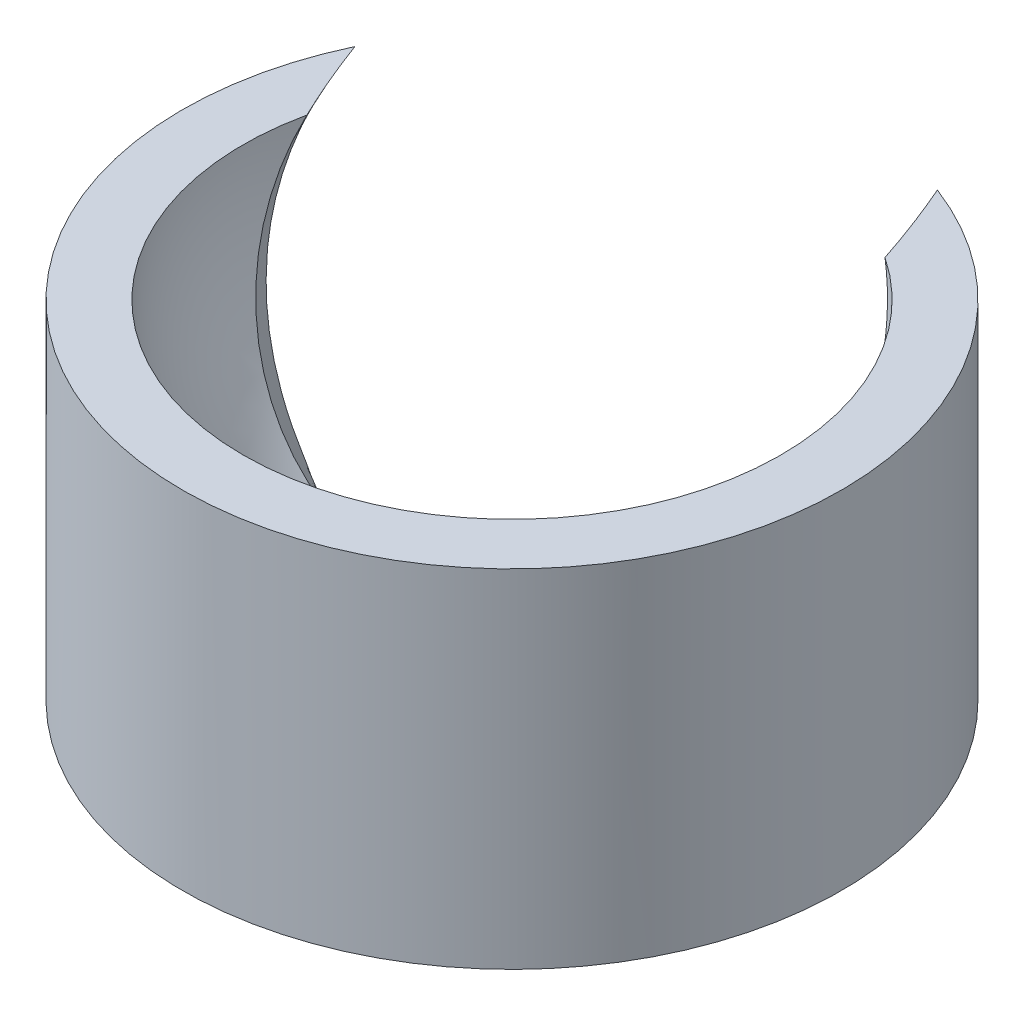
SolidWorks part; units mm, degrees
other "Moving Steel Cup Liner 3"
other "Moving Steel Cup Liner 3 Left"
ref_plane "Front Plane" through (0, 0, 0) normal (0, 0, 1) x (1, 0, 0)
ref_plane "Top Plane" through (0, 0, 0) normal (0, 1, 0) x (1, 0, 0)
ref_plane "Right Plane" through (0, 0, 0) normal (1, 0, 0) x (0, 0, -1)
sketch3d "Keyed Back Sketch datum points"
  point P0 (-56.2917, -97, 0)
  point P1 (-46.2917, -97, 0)
  point P2 (-56.2917, -97, 10)
ref_plane "Keyed Back Sketch plane" through (0, -97, 0) normal (0, -1, 0) x (-1, 0, 0)
sketch "Keyed Back Sketch" plane through (0, -97, 0) normal (0, -1, 0) x (-1, 0, 0)
  line L0 (59.8116, -28.5681) -> (55.7718, -26.2357)
  arc A0 (55.7718, -26.2357) -> (59.8116, -28.5681) centre (56.2917, -30) ccw
extrude "Keyed Back" add sketch "Keyed Back Sketch" along normal blind 0.7 separate body
sketch3d "Cup Blank Sketch datum points"
  point P0 (-56.2917, -97.7, 0)
  point P1 (-46.2917, -97.7, 0)
  point P2 (-56.2917, -97.7, 10)
ref_plane "Cup Blank Sketch plane" through (0, -97.7, 0) normal (0, -1, 0) x (-1, 0, 0)
sketch "Cup Blank Sketch" plane through (0, -97.7, 0) normal (0, -1, 0) x (-1, 0, 0)
  circle A0 centre (56.2917, -30) radius 3.8
extrude "Cup Blank" add sketch "Cup Blank Sketch" along normal blind 3.3
sketch3d "Spherical Bearing Seat axis line"
  line L0 (-56.2917, -101, 20) -> (-56.2917, -101, 40) construction
ref_axis "Spherical Bearing Seat axis" through (-56.2917, -101, 20) along (0, 0, 1)
sketch3d "Spherical Bearing Seat profile datum points"
  point P0 (-56.2917, -101, 30)
  point P1 (-46.2917, -101, 30)
  point P2 (-56.2917, -101, 40)
ref_plane "Spherical Bearing Seat profile plane" through (0, -101, 0) normal (0, -1, 0) x (-1, 0, 0)
sketch "Spherical Bearing Seat profile" plane through (0, -101, 0) normal (0, -1, 0) x (-1, 0, 0)
  line L0 (56.2917, -33.1) -> (56.2917, -26.9)
  arc A0 (56.2917, -26.9) -> (56.2917, -33.1) centre (56.2917, -30) ccw
revolve "Spherical Bearing Seat" cut sketch "Spherical Bearing Seat profile" angle 360 about axis through (-56.2917, -101, 20) along (0, 0, 1)
sketch3d "Articulation Throat axis line"
  line L0 (-53.1481, -106.3831, 37.8192) -> (-59.4352, -95.6169, 22.1808) construction
ref_axis "Articulation Throat axis" through (-53.1481, -106.3831, 37.8192) along (-0.3144, 0.5383, -0.7819)
sketch3d "Articulation Throat Sketch datum points"
  point P0 (-56.2917, -101, 30)
  point P1 (-56.2917, -109.2368, 24.3295)
  point P2 (-59.4352, -95.6169, 22.1808)
ref_plane "Articulation Throat Sketch plane" through (-75.1941, -14.1195, 20.5094) normal (0.9493, 0.1783, -0.2589) x (-0.2545, -0.0478, -0.9659)
sketch "Articulation Throat Sketch" plane through (-75.1941, -14.1195, 20.5094) normal (0.9493, 0.1783, -0.2589) x (-0.2545, -0.0478, -0.9659)
  line L0 (-9.8257, -88.8766) -> (-8.4754, -90.7385)
  line L1 (-8.4754, -90.7385) -> (14.089, -82.6758)
  line L2 (14.089, -82.6758) -> (8.7936, -75.3739)
  line L3 (8.7936, -75.3739) -> (-9.8257, -88.8766)
revolve "Articulation Throat" cut sketch "Articulation Throat Sketch" angle 360 about axis through (-53.1481, -106.3831, 37.8192) along (-0.3144, 0.5383, -0.7819)
sketch3d "Mirror1 profile datum points"
  point P0 (0, 0, 0)
  point P1 (10, 0, 0)
  point P2 (0, 0, 10)
ref_plane "Mirror1 profile plane" through (0, 0, 0) normal (0, -1, 0) x (-1, 0, 0)
mirror "Mirror1" about plane through (0, 0, 0) normal (0, -1, 0) of bodies 104
delete or keep bodies "Remove1" type delete bodies bodies 104
